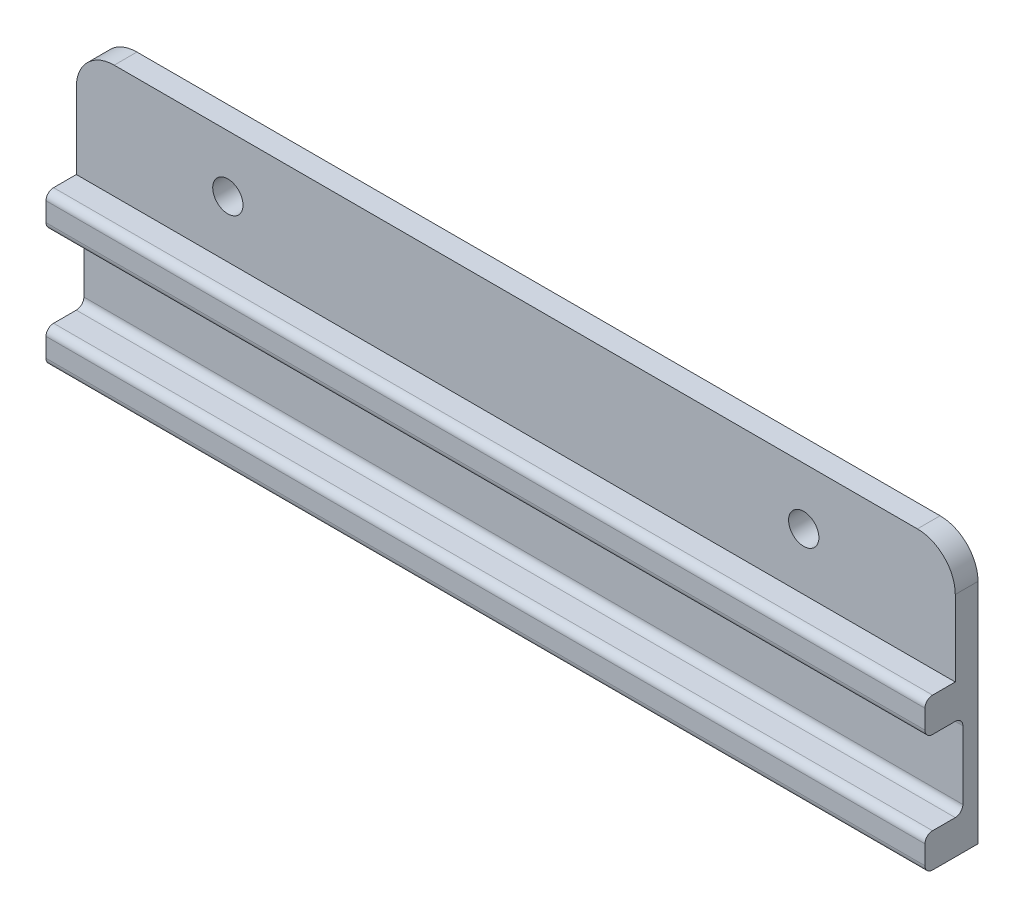
SolidWorks part; units mm, degrees
ref_plane "Front Plane" through (0, 0, 0) normal (0, 0, 1) x (1, 0, 0)
ref_plane "Top Plane" through (0, 0, 0) normal (0, 1, 0) x (1, 0, 0)
ref_plane "Right Plane" through (0, 0, 0) normal (1, 0, 0) x (0, 0, -1)
sketch "Sketch1" plane through (0, 0, 0) normal (0, 0, 1) x (1, 0, 0)
  line L1 (0, 0) -> (116, 0)
  line L2 (0, 0) -> (0, 20)
  line L3 (0, 20) -> (116, 20)
  line L4 (116, 0) -> (116, 20)
extrude "Boss-Extrude1" add sketch "Sketch1" along normal blind 2
sketch "Sketch2" plane through (0, 0, 2) normal (0, 0, 1) x (1, 0, 0)
  line L0 (116, 0) -> (116, 20) construction
  line L1 (0, 20) -> (116, 20)
  line L2 (0, 20) -> (0, 15.5)
  line L3 (0, 15.5) -> (116, 15.5)
  line L4 (116, 20) -> (116, 15.5)
  line L6 (0, 0) -> (116, 0)
  line L7 (0, 0) -> (0, 4.5)
  line L8 (0, 4.5) -> (116, 4.5)
  line L9 (116, 0) -> (116, 4.5)
  dimension "D1" = 4.5
  dimension "D2" = 4.5
extrude "Boss-Extrude2" add sketch "Sketch2" along normal blind 5
fillet "Fillet1" radius 1 6 edges at (58, 4.5, 2) (58, 15.5, 2) (58, 20, 7) (58, 0, 7) (58, 4.5, 7) (58, 15.5, 7)
sketch "Sketch3" plane through (0, 20, 0) normal (0, 1, 0) x (1, 0, 0)
  line L0 (116, -6) -> (116, 0) construction
  line L1 (0, 0) -> (116, 0)
  line L2 (0, 0) -> (0, -3)
  line L3 (0, -3) -> (116, -3)
  line L4 (116, 0) -> (116, -3)
extrude "Boss-Extrude3" add sketch "Sketch3" along normal blind 15
fillet "Fillet2" radius 5 2 edges at (116, 35, 1.5) (0, 35, 1.5)
sketch "Sketch4" plane through (0, 0, 3) normal (0, 0, 1) x (1, 0, 0)
  line L0 (58, 35) -> (58, 20) construction
  line L1 (5, 35) -> (111, 35) construction
  line L2 (0, 20) -> (116, 20) construction
  line L3 (58, 20) -> (58, 27.5) construction
  line L4 (58, 27.5) -> (111, 27.5) construction
  line L5 (116, 30) -> (116, 20) construction
  circle A0 centre (96, 27.5) radius 2
  circle A1 centre (20, 27.5) radius 2
  dimension "D1" = 4
  dimension "D2" = 20
extrude "Cut-Extrude1" cut sketch "Sketch4" against normal blind 15
